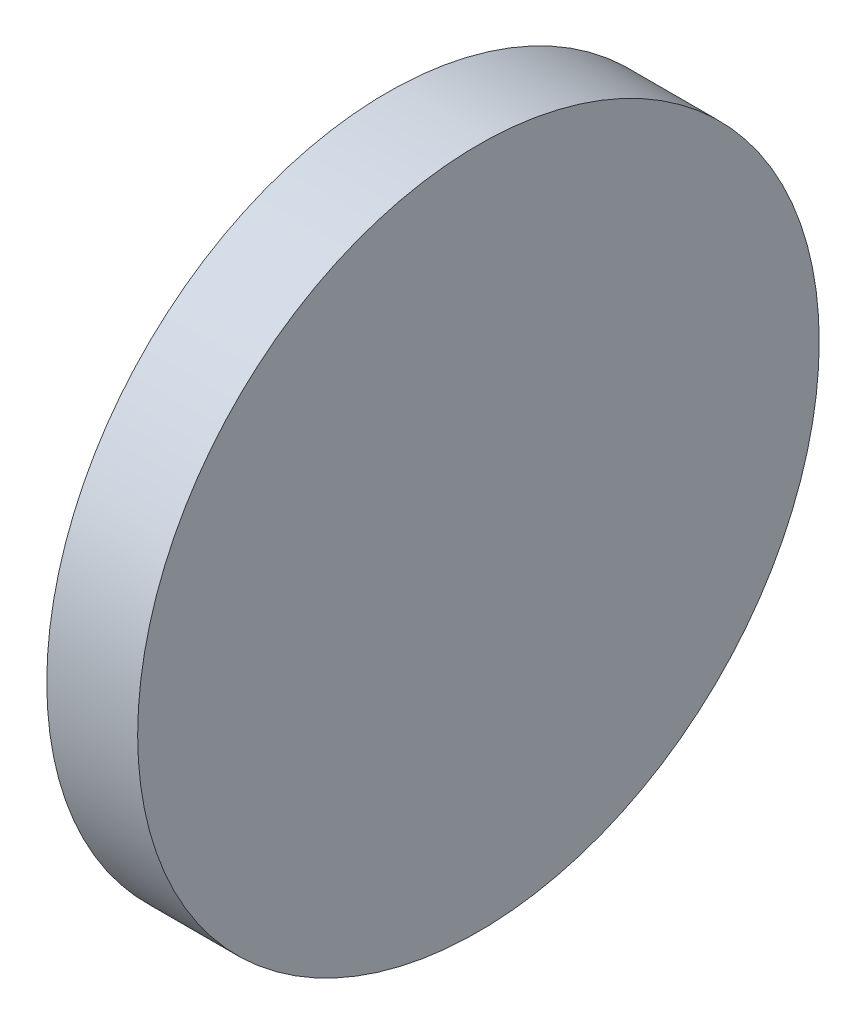
SolidWorks part; units mm, degrees
ref_plane "Front Plane" through (0, 0, 0) normal (0, 0, 1) x (1, 0, 0)
ref_plane "Top Plane" through (0, 0, 0) normal (0, 1, 0) x (1, 0, 0)
ref_plane "Right Plane" through (0, 0, 0) normal (1, 0, 0) x (0, 0, -1)
other "Configuration Table"
sketch "Sketch1" plane through (0, 0, 0) normal (1, 0, 0) x (0, 0, -1)
  circle A0 centre (0, 0) radius 7.5
  dimension "D1" = 15
extrude "Boss-Extrude1" add sketch "Sketch1" along normal blind 2
sketch "Sketch2" plane through (0, 0, 0) normal (-1, 0, 0) x (0, 0, 1)
  circle A0 centre (0, 0) radius 1
  dimension "D1" = 2
equation "\"radius\"= 12"
